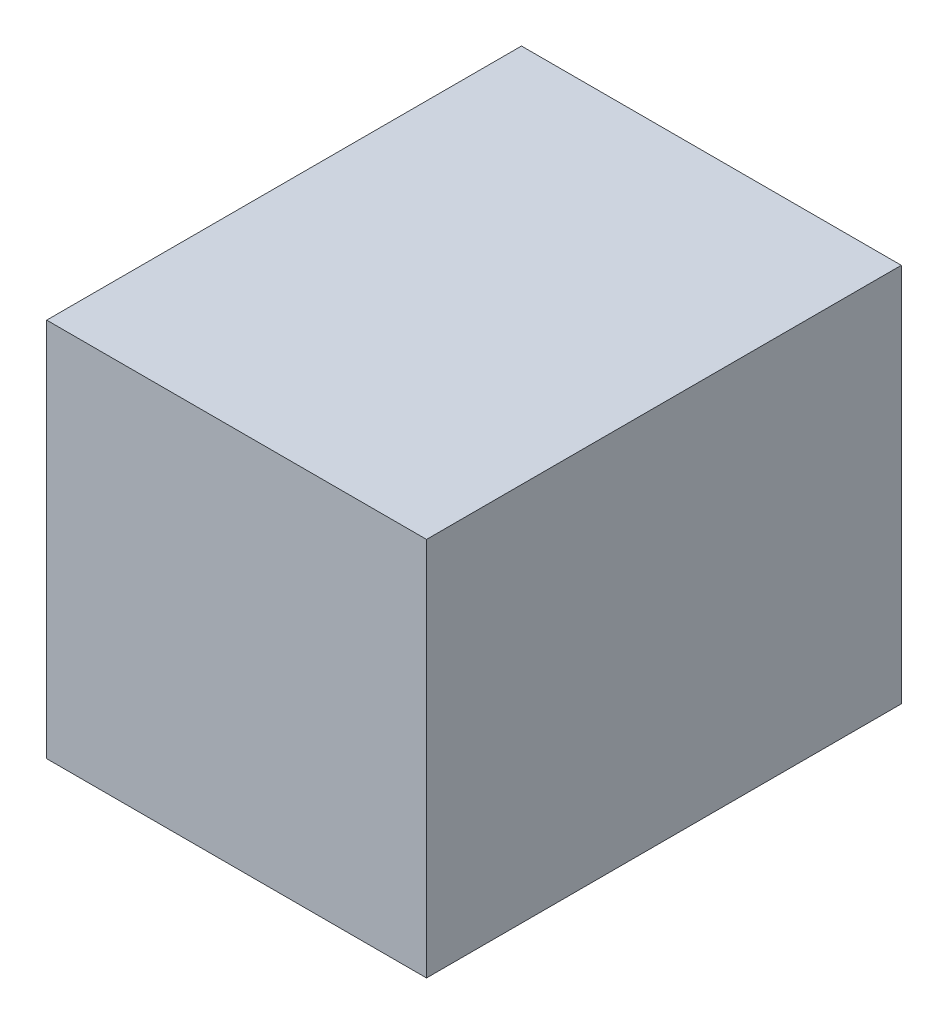
SolidWorks part; units mm, degrees
ref_plane "Plan de face" through (0, 0, 0) normal (0, 0, 1) x (1, 0, 0)
ref_plane "Plan de dessus" through (0, 0, 0) normal (0, 1, 0) x (1, 0, 0)
ref_plane "Plan de droite" through (0, 0, 0) normal (1, 0, 0) x (0, 0, -1)
sketch "Esquisse1" plane through (0, 0, 0) normal (0, 0, 1) x (1, 0, 0)
  line L1 (0, 0) -> (8, 0)
  line L2 (0, 0) -> (0, 8)
  line L3 (0, 8) -> (8, 8)
  line L4 (8, 0) -> (8, 8)
  dimension "D1" = 8
  dimension "D2" = 8
extrude "Boss.-Extru.1" add sketch "Esquisse1" along normal blind 10
